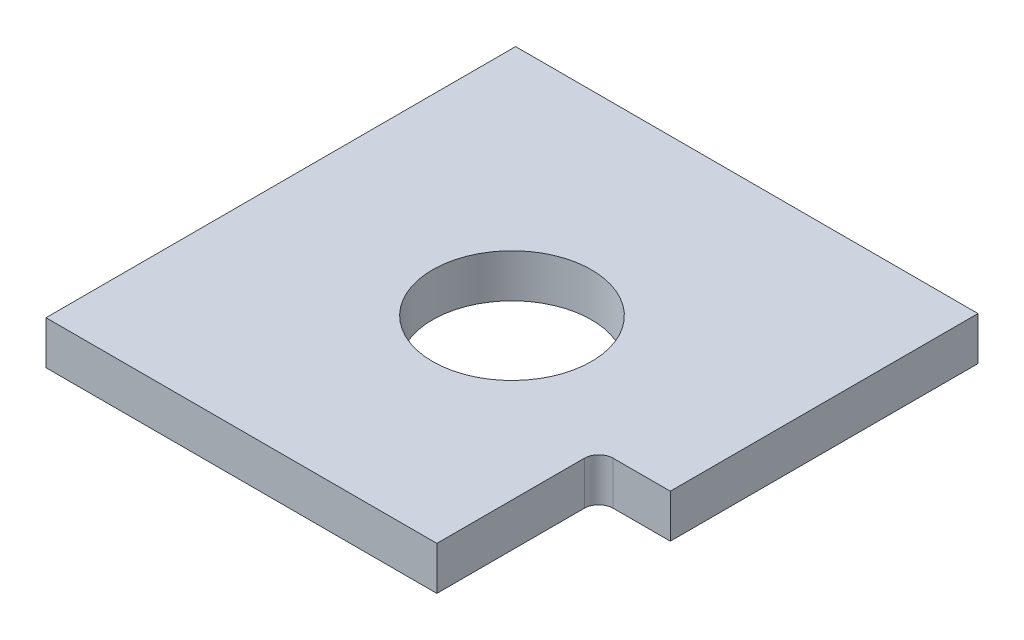
SolidWorks part; units mm, degrees
ref_plane "Front Plane" through (0, 0, 0) normal (0, 0, 1) x (1, 0, 0)
ref_plane "Top Plane" through (0, 0, 0) normal (0, 1, 0) x (1, 0, 0)
ref_plane "Right Plane" through (0, 0, 0) normal (1, 0, 0) x (0, 0, -1)
sketch "Sketch2" plane through (0, 0, 0) normal (0, 1, 0) x (1, 0, 0)
  line L0 (22.1, -32.5) -> (-32, -32.5)
  line L1 (22.1, -32.5) -> (22.1, -12.0891)
  line L2 (24.1, -10.0891) -> (32, -10.0891)
  line L3 (32, 32.5) -> (32, -10.0891)
  line L4 (-32, 32.5) -> (32, 32.5)
  line L5 (-32, -32.5) -> (-32, 32.5)
  circle A0 centre (0, 0) radius 11
  arc A1 (24.1, -10.0891) -> (22.1, -12.0891) centre (24.1, -12.0891) ccw
  point P10 (0, 0)
  point P11 (0, 0)
  point P14 (0, 0)
  dimension "D7" = 2
  dimension "D8" = 22
  dimension "D1" = 42.5891
  dimension "D2" = 64
  dimension "D3" = 65
  dimension "D4" = 20.4109
  dimension "D5" = 7.9
  dimension "D6" = 54.1
  dimension "D9" = 32
  dimension "D10" = 32.5
extrude "Boss-Extrude1" add sketch "Sketch2" along normal blind 6 separate body
